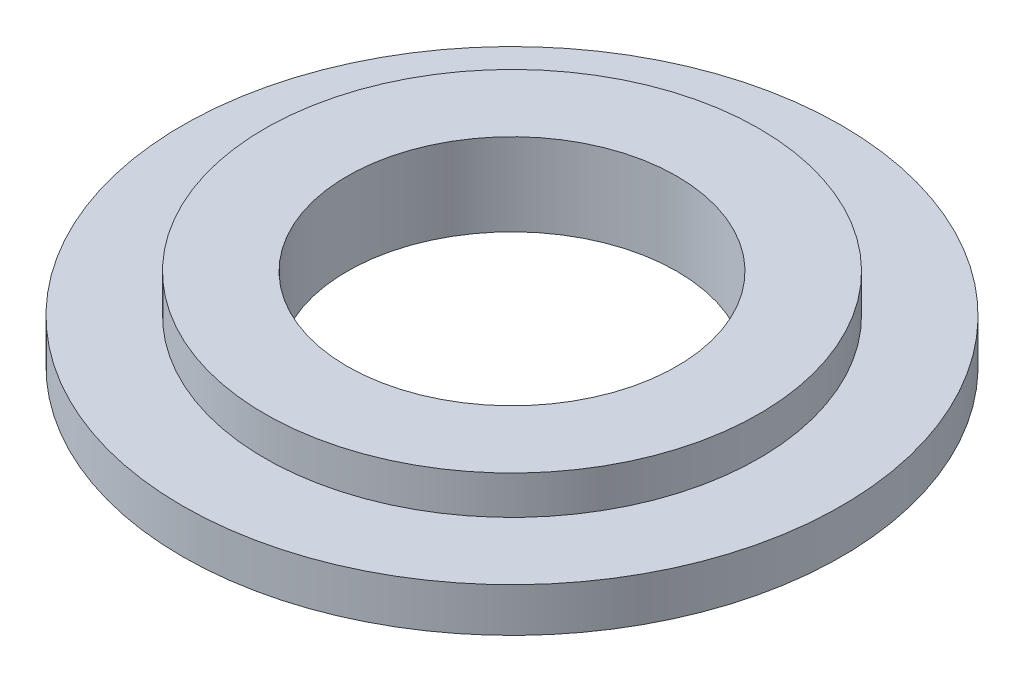
SolidWorks part; units mm, degrees
ref_plane "Front Plane" through (0, 0, 0) normal (0, 0, 1) x (1, 0, 0)
ref_plane "Top Plane" through (0, 0, 0) normal (0, 1, 0) x (1, 0, 0)
ref_plane "Right Plane" through (0, 0, 0) normal (1, 0, 0) x (0, 0, -1)
sketch "Sketch2" plane through (0, 0, 0) normal (1, 0, 0) x (0, 0, -1)
  line L0 (-15, 0) -> (-7.5, 0)
  line L1 (-15, 2) -> (-11.25, 2)
  line L2 (-15, 2) -> (-15, 0)
  line L5 (0, -1000) -> (0, 49000) construction
  line L7 (-11.25, 3.75) -> (-7.5, 3.75)
  line L8 (-11.25, 3.75) -> (-11.25, 2)
  line L10 (-7.5, 3.75) -> (-7.5, 0)
  point P0 (-17.0282, 0.936)
  point P5 (-10.1277, 1.4107)
  dimension "D1" = 7.5
  dimension "D2" = 15
  dimension "D3" = 7.5
  dimension "D4" = 3.75
  dimension "D5" = 3.75
  dimension "D6" = 2
  dimension "D7" = 3.75
revolve "Revolve1" add sketch "Sketch2" angle 360 about L5
